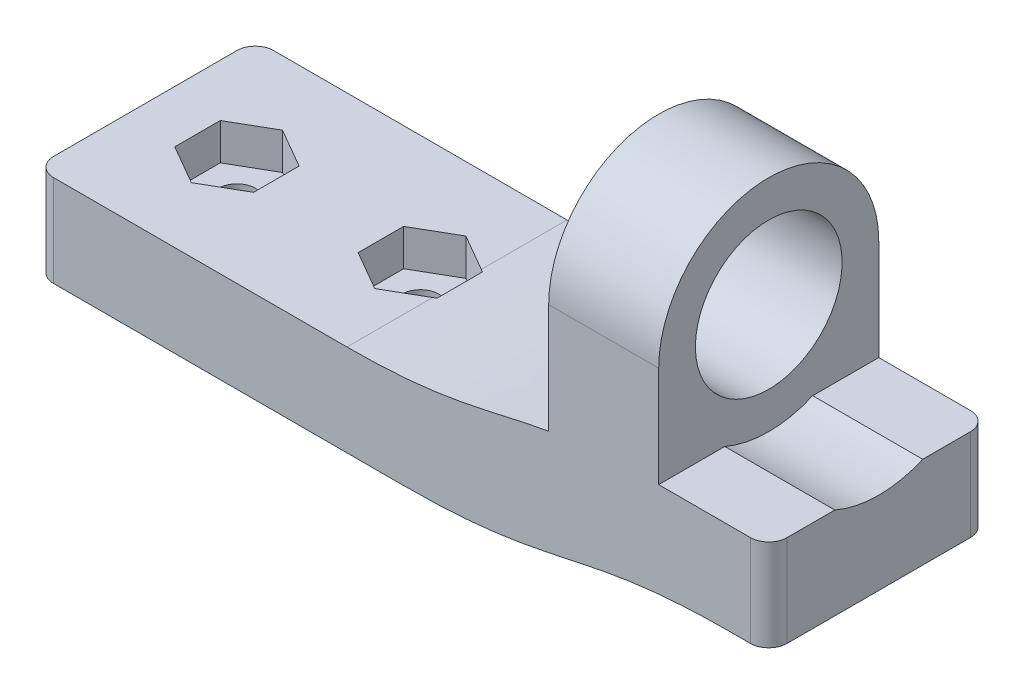
SolidWorks part; units mm, degrees
ref_plane "Front Plane" through (0, 0, 0) normal (0, 0, 1) x (1, 0, 0)
ref_plane "Top Plane" through (0, 0, 0) normal (0, 1, 0) x (1, 0, 0)
ref_plane "Right Plane" through (0, 0, 0) normal (1, 0, 0) x (0, 0, -1)
sketch "Sketch1" plane through (0, 0, 0) normal (0, 0, 1) x (1, 0, 0)
  line L0 (0, 0) -> (0, 5)
  line L1 (0, 5) -> (17, 5)
  line L2 (0, 0) -> (20, 0)
  line L3 (40, 2) -> (38, 2)
  line L4 (40, 2) -> (40, 7)
  line L5 (40, 7) -> (34, 7)
  line L6 (34, 7) -> (34, 18.5)
  line L7 (34, 18.5) -> (28, 18.5)
  line L8 (28, 18.5) -> (28, 6.5192)
  line L9 (34, 12.5) -> (28, 12.5) construction
  spline S0 degree 3 poles (20, 0) (28.6897, 0) (29.3402, 2) (38, 2) knots 0 0 0 0 1 1 1 1
  spline S1 degree 3 poles (17, 5) (25.0494, 5) (25.9185, 7) (34, 7) knots 0 0 0 0 1 1 1 1
  dimension "D1" = 5
  dimension "D2" = 20
  dimension "D3" = 20
  dimension "D4" = 12.5
  dimension "D5" = 6
  dimension "D6" = 6
  dimension "D7" = 6
  dimension "D8" = 2
  dimension "D9" = 2
  dimension "D10" = 17
  dimension "D11" = 2
  dimension "D12" = 5
extrude "Boss-Extrude1" add sketch "Sketch1" along normal blind 12 contours S1 L1 L0 L2 S0 L3 L4 L5 | L9 L6 L7 L8 | L6 L9 L8 S1 L5
sketch "Sketch2" plane through (0, 0, 0) normal (1, 0, 0) x (0, 0, -1)
  line L0 (-12, 0) -> (0, 0) construction
  line L1 (-6, 0) -> (-6, 12.5) construction
  line L2 (0, 18.5) -> (0, 6.5192) construction
  line L3 (-12, 18.5) -> (0, 18.5) construction
  line L4 (-12, 18.5) -> (-12, 6.5192) construction
  line L5 (0, 18.5) -> (0, 6.5192)
  line L6 (-12, 18.5) -> (0, 18.5)
  line L7 (-12, 18.5) -> (-12, 6.5192)
  circle A0 centre (-6, 12.5) radius 4
  circle A1 centre (-6, 12.5) radius 6
  dimension "D2" = 8
  dimension "D1" = 12.5
extrude "Cut-Extrude1" cut sketch "Sketch2" along normal through all
sketch "Sketch3" plane through (0, 0, 0) normal (0, 1, 0) x (1, 0, 0)
  line L0 (0, -6) -> (40, -6) construction
  line L1 (0, -12) -> (0, 0) construction
  line L2 (40, -12) -> (40, 0) construction
  circle A0 centre (15, -6) radius 1
  circle A1 centre (5, -6) radius 1
  dimension "D3" = 2
  dimension "D4" = 2
  dimension "D1" = 10
  dimension "D2" = 25
extrude "Cut-Extrude2" cut sketch "Sketch3" along normal through all
fillet "Fillet2" radius 1 4 edges at (40, 4.5, 12) (40, 4.5, 0) (0, 2.5, 12) (0, 2.5, 0)
sketch "Sketch5" plane through (34, 0, 0) normal (1, 0, 0) x (0, 0, -1)
  circle A0 centre (-6, 12.5) radius 6
extrude "Cut-Extrude3" cut sketch "Sketch5" along normal blind 10
sketch "Sketch6" plane through (0, 5, 0) normal (0, 1, 0) x (1, 0, 0)
  line L1 (12.85, -4.7587) -> (12.85, -7.2413)
  line L2 (12.85, -7.2413) -> (15, -8.4826)
  line L3 (15, -8.4826) -> (17.15, -7.2413)
  line L4 (17.15, -7.2413) -> (17.15, -4.7587)
  line L5 (17.15, -4.7587) -> (15, -3.5174)
  line L6 (15, -3.5174) -> (12.85, -4.7587)
  line L7 (5, -3.5174) -> (2.85, -4.7587)
  line L8 (2.85, -4.7587) -> (2.85, -7.2413)
  line L9 (2.85, -7.2413) -> (5, -8.4826)
  line L10 (5, -8.4826) -> (7.15, -7.2413)
  line L11 (7.15, -7.2413) -> (7.15, -4.7587)
  line L12 (7.15, -4.7587) -> (5, -3.5174)
  circle A0 centre (15, -6) radius 2.15 construction
  circle A1 centre (5, -6) radius 2.15 construction
  dimension "D1" = 4.3
extrude "Cut-Extrude4" cut sketch "Sketch6" against normal blind 2 and the other way blind 1
